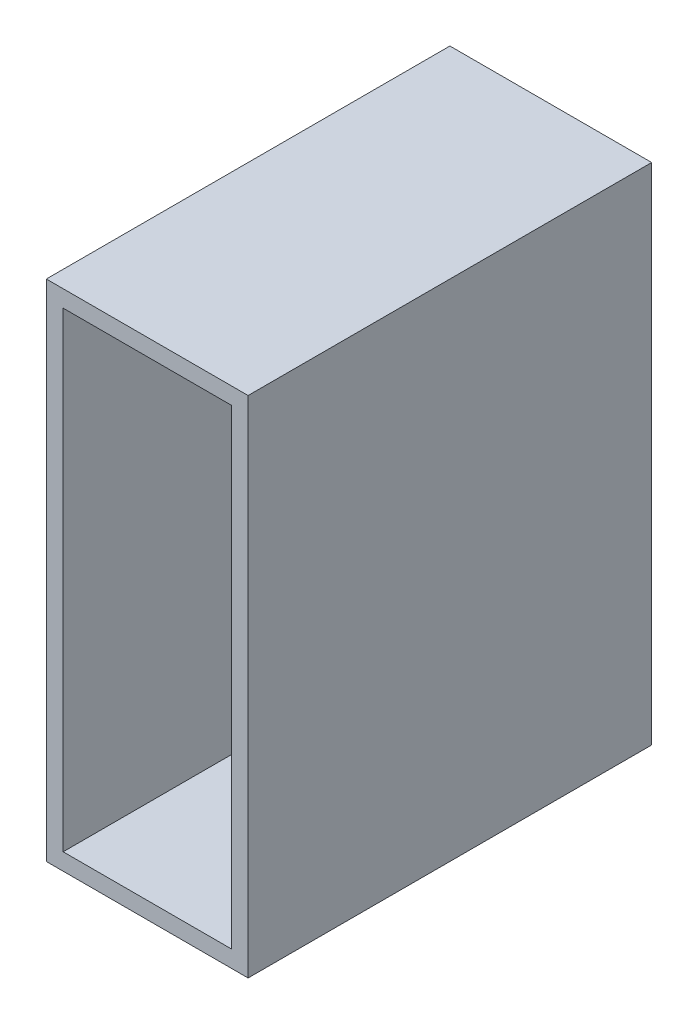
SolidWorks part; units mm, degrees
ref_plane "Front Plane" through (0, 0, 0) normal (0, 0, 1) x (1, 0, 0)
ref_plane "Top Plane" through (0, 0, 0) normal (0, 1, 0) x (1, 0, 0)
ref_plane "Right Plane" through (0, 0, 0) normal (1, 0, 0) x (0, 0, -1)
sketch "Sketch1" plane through (0, 0, 0) normal (0, 0, 1) x (1, 0, 0)
  line L1 (0, 0) -> (24, 0)
  line L2 (0, 0) -> (0, 60)
  line L3 (0, 60) -> (24, 60)
  line L4 (24, 0) -> (24, 60)
  line L6 (2, 2) -> (22, 2)
  line L7 (2, 2) -> (2, 58)
  line L8 (2, 58) -> (22, 58)
  line L9 (22, 2) -> (22, 58)
  dimension "D2" = 22
  dimension "D3" = 24
  dimension "D4" = 2
  dimension "D5" = 58
  dimension "D6" = 60
extrude "Profile" add sketch "Sketch1" along normal blind 48
sketch "Sketch2" plane through (0, 0, 0) normal (0, 0, 1) x (1, 0, 0)
  line L1 (2, 2) -> (22, 2)
  line L2 (2, 2) -> (2, 58)
  line L3 (2, 58) -> (22, 58)
  line L4 (22, 2) -> (22, 58)
  dimension "D1" = 20
  dimension "D2" = 56
extrude "Back" add sketch "Sketch2" along normal blind 2
equation "\"Profile_Depth\"= 48mm"
equation "\"D1@Profile\" = \"Profile_Depth\""
equation "\"Profile_Sketch_1\"= 2mm"
equation "\"D1@Sketch1\" = \"Profile_Sketch_1\""
equation "\"Profile_Sketch_2\"= 22mm"
equation "\"D2@Sketch1\" = \"Profile_Sketch_2\""
equation "\"Profile_Sketch_3\"= 24mm"
equation "\"D3@Sketch1\" = \"Profile_Sketch_3\""
equation "\"Profile_Sketch_4\"= 2mm"
equation "\"D4@Sketch1\" = \"Profile_Sketch_4\""
equation "\"Profile_Sketch_5\"= 58mm"
equation "\"D5@Sketch1\" = \"Profile_Sketch_5\""
equation "\"Profile_Sketch_6\"= 60mm"
equation "\"D6@Sketch1\" = \"Profile_Sketch_6\""
equation "\"Back_Depth\"= 2mm"
equation "\"D1@Back\" = \"Back_Depth\""
equation "\"Back_Sketch_1\"= 20mm"
equation "\"D1@Sketch2\" = \"Back_Sketch_1\""
equation "\"Back_Sketch_2\"= 56mm"
equation "\"D2@Sketch2\" = \"Back_Sketch_2\""
equation "\"EnvelopeWidth\"= 24mm"
equation "\"EnvelopeHeight\"= 60mm"
